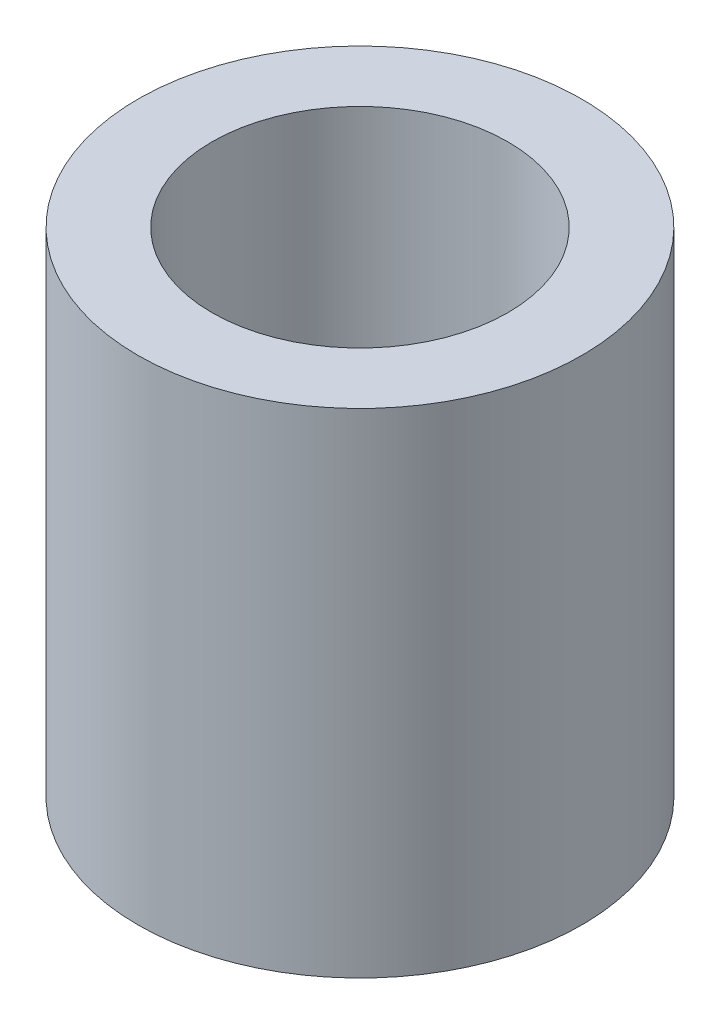
SolidWorks part; units mm, degrees
ref_plane "Front Plane" through (0, 0, 0) normal (0, 0, 1) x (1, 0, 0)
ref_plane "Top Plane" through (0, 0, 0) normal (0, 1, 0) x (1, 0, 0)
ref_plane "Right Plane" through (0, 0, 0) normal (1, 0, 0) x (0, 0, -1)
sketch "Sketch1" plane through (0, 0, 0) normal (0, 1, 0) x (1, 0, 0)
  circle A0 centre (0, 0) radius 4.5
  circle A1 centre (0, 0) radius 3
  dimension "D1" = 9
  dimension "D2" = 6
extrude "Boss-Extrude3" add sketch "Sketch1" along normal blind 10
sketch "Sketch4" plane through (0, 10, 0) normal (0, 1, 0) x (1, 0, 0)
  line L0 (5.1552, 4.0306) -> (3.6942, 2.5696)
  line L1 (-1.2047, 6.4953) -> (0.7953, 6.4953)
  line L2 (0.7953, 6.4953) -> (0.7953, 4.4292)
  line L3 (-1.2047, 6.4953) -> (-1.2047, 4.3357)
  line L4 (3.741, 5.4448) -> (2.2139, 3.9177)
  line L5 (3.741, 5.4448) -> (5.1552, 4.0306)
  line L6 (6.4953, -0.7953) -> (4.4292, -0.7953)
  line L7 (6.4953, 1.2047) -> (4.3357, 1.2047)
  line L8 (6.4953, 1.2047) -> (6.4953, -0.7953)
  line L9 (4.0306, -5.1552) -> (2.5696, -3.6942)
  line L10 (5.4448, -3.741) -> (3.9177, -2.2139)
  line L11 (5.4448, -3.741) -> (4.0306, -5.1552)
  line L12 (-0.7953, -6.4953) -> (-0.7953, -4.4292)
  line L13 (1.2047, -6.4953) -> (1.2047, -4.3357)
  line L14 (1.2047, -6.4953) -> (-0.7953, -6.4953)
  line L15 (-5.1552, -4.0306) -> (-3.6942, -2.5696)
  line L16 (-3.741, -5.4448) -> (-2.2139, -3.9177)
  line L17 (-3.741, -5.4448) -> (-5.1552, -4.0306)
  line L18 (-6.4953, 0.7953) -> (-4.4292, 0.7953)
  line L19 (-6.4953, -1.2047) -> (-4.3357, -1.2047)
  line L20 (-6.4953, -1.2047) -> (-6.4953, 0.7953)
  line L21 (-4.0306, 5.1552) -> (-2.5696, 3.6942)
  line L22 (-5.4448, 3.741) -> (-3.9177, 2.2139)
  line L23 (-5.4448, 3.741) -> (-4.0306, 5.1552)
  circle A0 centre (0, 0) radius 4.5 construction
  point P37 (0, 0)
  dimension "D1" = 8
